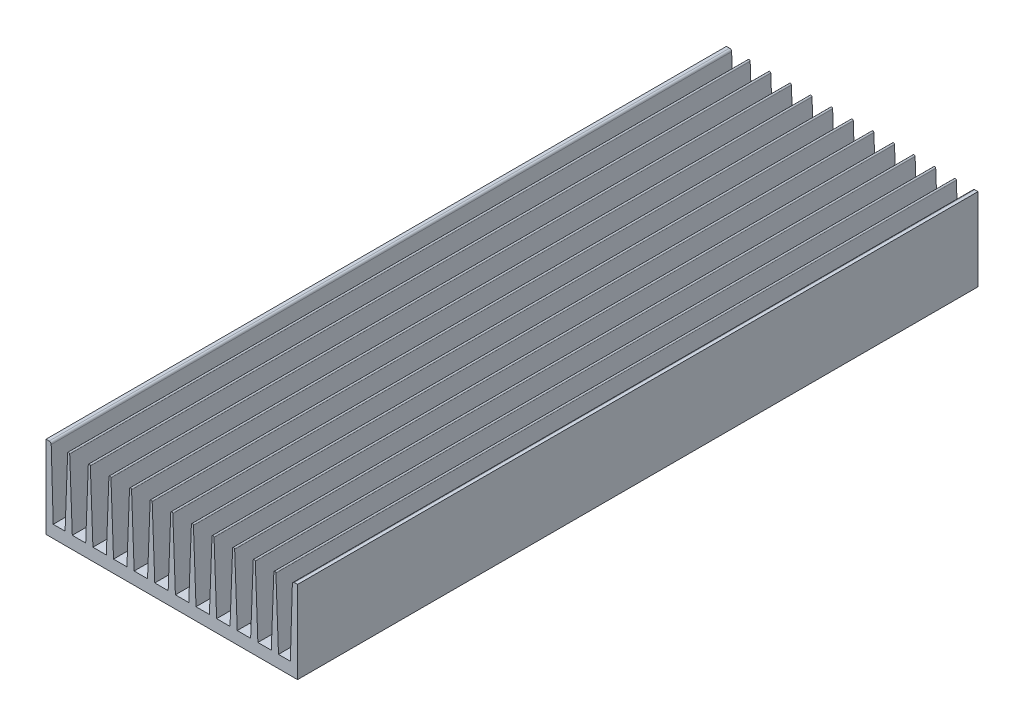
SolidWorks part; units mm, degrees
ref_plane "Спереди" through (0, 0, 0) normal (0, 0, 1) x (1, 0, 0)
ref_plane "Сверху" through (0, 0, 0) normal (0, 1, 0) x (1, 0, 0)
ref_plane "Справа" through (0, 0, 0) normal (1, 0, 0) x (0, 0, -1)
sketch "Эскиз1" plane through (0, 0, 0) normal (0, 0, 1) x (1, 0, 0)
  line L0 (0, 40) -> (1.529, 40)
  line L1 (0, 0) -> (122, 0)
  line L2 (2.5285, 39.0294) -> (3.5, 6)
  line L3 (0, 40) -> (0, 0)
  line L4 (122, 40) -> (122, 0)
  line L5 (61, 63.7127) -> (61, -22.2582) construction
  line L8 (122, 40) -> (120.471, 40)
  line L9 (119.4715, 39.0294) -> (118.5, 6)
  line L10 (3.5, 6) -> (118.5, 6)
  arc A0 (1.529, 40) -> (2.5285, 39.0294) centre (1.529, 39) cw
  arc A2 (120.471, 40) -> (119.4715, 39.0294) centre (120.471, 39) ccw
  point P18 (119.5, 40)
  dimension "D9" = 1
  dimension "D1" = 122
  dimension "D2" = 6
  dimension "D3" = 40
  dimension "D4" = 3.5
  dimension "D7" = 2.5
extrude "Вытянуть1" add sketch "Эскиз1" along normal blind 330
sketch "Эскиз2" plane through (0, 0, 330) normal (0, 0, 1) x (1, 0, 0)
  line L0 (118.5, 6) -> (3.5, 6) construction
  line L1 (10.5, 39.5) -> (9.25, 6)
  line L2 (11, 39.5) -> (11, 22.5548) construction
  line L3 (11.5, 39.5) -> (12.75, 6)
  line L4 (9.25, 6) -> (12.75, 6)
  line L6 (0, 40) -> (0, 0) construction
  arc A0 (10.5, 39.5) -> (11.5, 39.5) centre (11, 39.5) cw
  dimension "D1" = 34
  dimension "D3" = 0.5
  dimension "D2" = 3.5
  dimension "D4" = 11
  dimension "D5" = 1
extrude "Вытянуть3" add sketch "Эскиз2" against normal blind 330
pattern_curve "Кривая1" of "Вытянуть3" along edge at (61, 0, 0) parameters "D1"=11, "D3"=10, "D2"=1, "D4"=50
sketch "Эскиз3" plane through (0, 0, 0) normal (0, -1, 0) x (1, 0, 0)
  line L0 (-14.0506, 322) -> (137.5079, 322) construction
  line L1 (0, 330) -> (122, 330) construction
  line L2 (0, 330) -> (0, 0) construction
  line L3 (-46.7511, 165) -> (151.4312, 165) construction
  line L4 (0, 0) -> (122, 0) construction
  circle A0 centre (28, 322) radius 2.25
  circle A1 centre (94, 322) radius 2.25
  circle A2 centre (94, 8) radius 2.25
  circle A3 centre (28, 8) radius 2.25
  dimension "D2" = 66
  dimension "D4" = 4.5
  dimension "D1" = 8
  dimension "D3" = 28
extrude "Вырез-Вытянуть1" cut sketch "Эскиз3" against normal blind 6
sketch "Эскиз4" plane through (1.488, 0, 27.4005) normal (0, -1, 0) x (1, 0, 0)
  line L0 (28.512, 156.5995) -> (28.512, 276.5995) construction
  line L1 (171.5072, 189.0995) -> (120.1328, 189.0995) construction
  line L3 (-1.488, 302.5995) -> (120.512, 302.5995) construction
  line L4 (59.512, 3.7951) -> (59.512, 109.5037) construction
  line L5 (-1.488, 302.5995) -> (-1.488, -27.4005) construction
  line L6 (-1.488, -27.4005) -> (120.512, -27.4005) construction
  line L7 (75.912, 200.0995) -> (75.912, 233.5995) construction
  circle A0 centre (75.912, 233.5995) radius 1.6
  circle A1 centre (59.512, 123.5995) radius 1.6
  circle A2 centre (75.912, 200.0995) radius 1.6
  circle A3 centre (28.512, 276.5995) radius 1.6
  circle A4 centre (28.512, 156.5995) radius 1.6
  circle A5 centre (59.512, 13.5995) radius 1.6
  circle A6 centre (38.512, 113.5995) radius 2.1
  circle A7 centre (65.832, 79.4795) radius 2.5
  circle A8 centre (100.512, 251.5995) radius 2.6
  circle A9 centre (85.842, 140.3995) radius 1.1
  dimension "D2" = 3.2
  dimension "D4" = 77.4
  dimension "D5" = 33.5
  dimension "D7" = 120
  dimension "D8" = 3.2
  dimension "D9" = 102
  dimension "D1" = 26
  dimension "D10" = 5.2
  dimension "D11" = 110
  dimension "D6" = 69
  dimension "D12" = 61
  dimension "D13" = 3.2
  dimension "D14" = 4.2
  dimension "D19" = 5
  dimension "D20" = 106.88
  dimension "D21" = 51
  dimension "D22" = 2.2
  dimension "D23" = 87.33
  dimension "D24" = 167.8
  dimension "D3" = 30
  dimension "D15" = 40
  dimension "D16" = 141
  dimension "D17" = 41
  dimension "D18" = 67.32
extrude "Вырез-Вытянуть2" cut sketch "Эскиз4" against normal blind 6
cosmetic thread "Условное изображение резьбы6" parameters "D2"=4
cosmetic thread "Условное изображение резьбы8" parameters "D2"=4
cosmetic thread "Условное изображение резьбы9" parameters "D1"=6, "D2"=4
cosmetic thread "Условное изображение резьбы10" parameters "D1"=6, "D2"=4
cosmetic thread "Условное изображение резьбы11" parameters "D1"=6, "D2"=5
cosmetic thread "Условное изображение резьбы12" parameters "D1"=6, "D2"=4
cosmetic thread "Условное изображение резьбы13" parameters "D1"=6, "D2"=4
cosmetic thread "Условное изображение резьбы14" parameters "D1"=6, "D2"=6
cosmetic thread "Условное изображение резьбы15"
